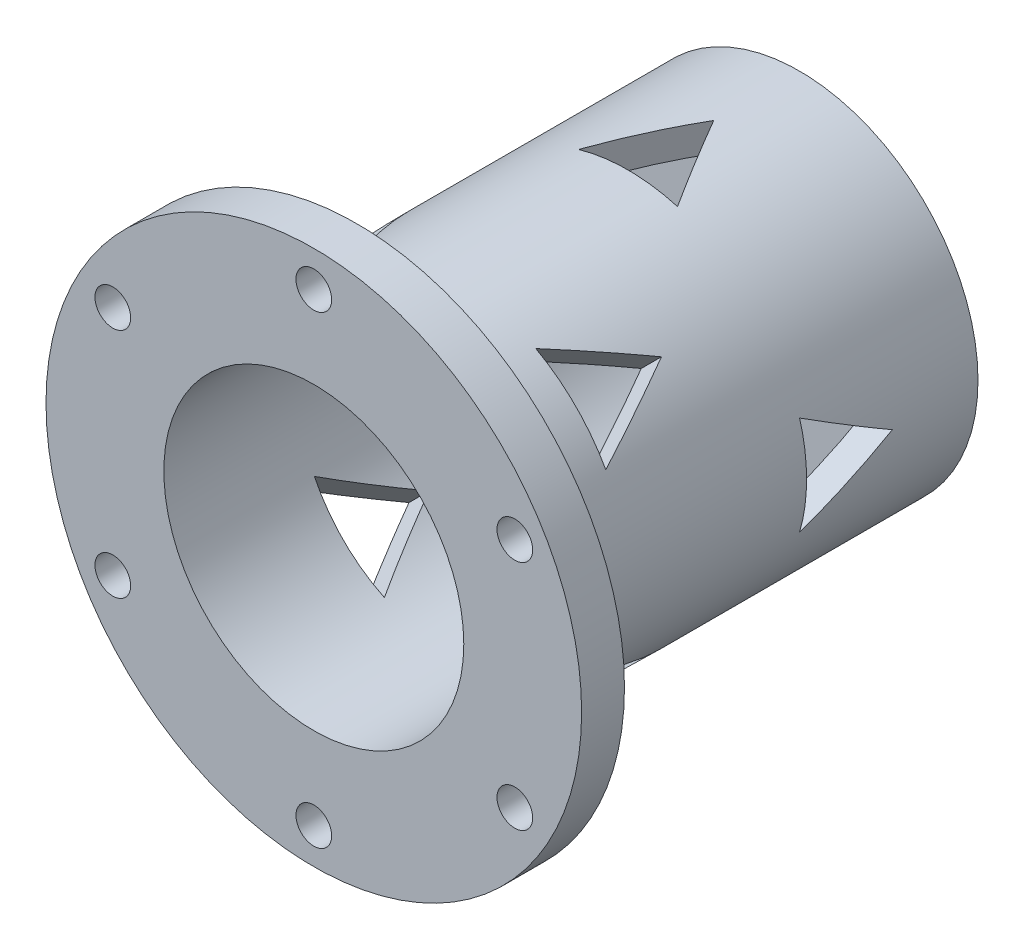
SolidWorks part; units mm, degrees
ref_plane "前视基准面" through (0, 0, 0) normal (0, 0, 1) x (1, 0, 0)
ref_plane "上视基准面" through (0, 0, 0) normal (0, 1, 0) x (1, 0, 0)
ref_plane "右视基准面" through (0, 0, 0) normal (1, 0, 0) x (0, 0, -1)
sketch "草图1" plane through (0, 0, 0) normal (0, 0, 1) x (1, 0, 0)
  circle A0 centre (0, 0) radius 25
  dimension "D1" = 50
extrude "凸台-拉伸1" add sketch "草图1" along normal blind 4
sketch "草图2" plane through (0, 0, 4) normal (0, 0, 1) x (1, 0, 0)
  circle A0 centre (0, 0) radius 25
  circle A1 centre (0, 0) radius 21
  dimension "D1" = 42
extrude "凸台-拉伸2" add sketch "草图2" along normal blind 64
sketch "草图3" plane through (0, 0, 68) normal (0, 0, 1) x (1, 0, 0)
  circle A0 centre (0, 0) radius 21
  circle A1 centre (0, 0) radius 37.5
  circle A2 centre (0, 0) radius 32.5 construction
  circle A3 centre (0, 32.5) radius 2.5
  circle A4 centre (28.1458, 16.25) radius 2.5
  circle A5 centre (28.1458, -16.25) radius 2.5
  circle A6 centre (0, -32.5) radius 2.5
  circle A7 centre (-28.1458, -16.25) radius 2.5
  circle A8 centre (-28.1458, 16.25) radius 2.5
  dimension "D1" = 75
  dimension "D2" = 5
  dimension "D3" = 65
  dimension "D4" = 6
extrude "凸台-拉伸3" add sketch "草图3" against normal blind 6
fillet "圆角1" radius 3 1 edges at (25, 0, 62)
sketch "草图4" plane through (0, 0, 0) normal (0, 0, -1) x (-1, 0, 0)
  line L0 (0, 0) -> (15.4258, 0) construction
  line L1 (0, 0) -> (0, -12.8039) construction
  circle A0 centre (0, 0) radius 4.25
  circle A2 centre (0, 9.25) radius 1.5
  circle A3 centre (7.75, 0) radius 1.5
  circle A4 centre (0, -9.25) radius 1.5
  circle A5 centre (-7.75, 0) radius 1.5
  dimension "D1" = 8.5
  dimension "D2" = 3
  dimension "D4" = 3
  dimension "D3" = 9.25
  dimension "D5" = 7.75
extrude "切除-拉伸1" cut sketch "草图4" against normal blind 5
sketch "草图5" plane through (0, 0, 0) normal (1, 0, 0) x (0, 0, -1)
  line L1 (-12, 0) -> (-24, 6.9282)
  line L2 (-24, 6.9282) -> (-24, -6.9282)
  line L3 (-24, -6.9282) -> (-12, 0)
  circle A0 centre (-20, 0) radius 4 construction
  dimension "D1" = 8
  dimension "D2" = 20
extrude "切除-拉伸2" cut sketch "草图5" against normal mid plane 100
pattern_circular "阵列(圆周)2" count 4 over 360 about axis through (0, 0, 0) along (0, 0, 1) of "切除-拉伸2"
sketch "草图6" plane through (0, 0, 0) normal (0, 0, -1) x (-1, 0, 0)
  line L0 (0, 0) -> (-17.6777, 17.6777)
  line L1 (0, 0) -> (-15.6953, 0)
  circle A0 centre (0, 0) radius 25 construction
  dimension "D1" = 45
ref_plane "基准面1" through (17.6777, 17.6777, 0) normal (0.7071, 0.7071, 0) x (0.7071, -0.7071, 0)
sketch "草图7" plane through (17.6777, 17.6777, 0) normal (0.7071, 0.7071, 0) x (0.7071, -0.7071, 0)
  line L0 (25, 0) -> (-25, 0) construction
  line L1 (0, -37) -> (-6.9282, -49)
  line L2 (-6.9282, -49) -> (6.9282, -49)
  line L3 (6.9282, -49) -> (0, -37)
  circle A0 centre (0, -45) radius 4 construction
  dimension "D1" = 8
  dimension "D2" = 45
extrude "切除-拉伸3" cut sketch "草图7" against normal blind 100
pattern_circular "阵列(圆周)3" count 4 over 360 about axis through (0, 0, 0) along (0, 0, 1) of "切除-拉伸3"
sketch "草图8" plane through (0, 0, 0) normal (0, 0, -1) x (-1, 0, 0)
  line L0 (0, 0) -> (0, 13.0005) construction
  line L1 (0, 0) -> (-14.8492, 14.8492)
  line L2 (0, 0) -> (14.8492, 14.8492)
  line L3 (0, 0) -> (-14.8492, -14.8492)
  line L4 (0, 0) -> (14.8492, -14.8492)
  circle A0 centre (0, 0) radius 17.5
  circle A1 centre (0, 0) radius 21
  dimension "D1" = 42
  dimension "D2" = 35
  dimension "D3" = 45
  dimension "D4" = 90
extrude "切除-拉伸4" cut sketch "草图8" against normal blind 2 contours L1 A1 L3 A0 | L4 A1 L2 A0
